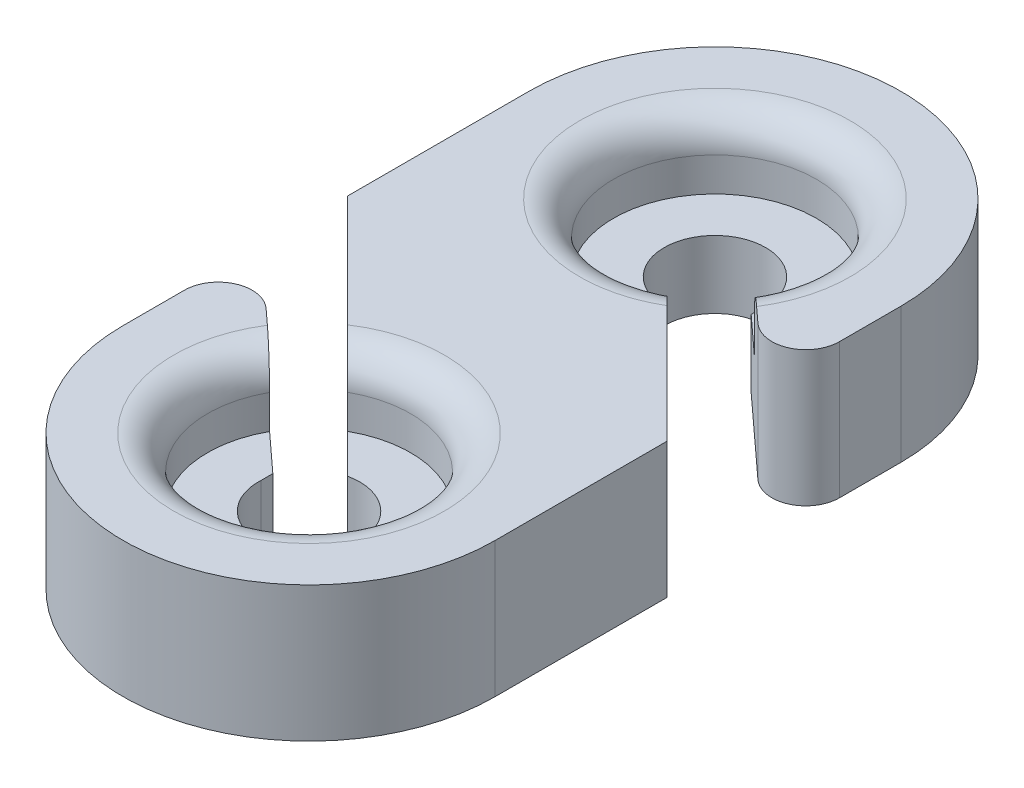
SolidWorks part; units mm, degrees
ref_plane "Front Plane" through (0, 0, 0) normal (0, 0, 1) x (1, 0, 0)
ref_plane "Top Plane" through (0, 0, 0) normal (0, 1, 0) x (1, 0, 0)
ref_plane "Right Plane" through (0, 0, 0) normal (1, 0, 0) x (0, 0, -1)
sketch "Sketch1" plane through (0, 0, 0) normal (0, 1, 0) x (1, 0, 0)
  line L0 (0, 6) -> (0, -6) construction
  line L1 (0, 6) -> (6, 0) construction
  line L2 (0, -6) -> (-6, 0) construction
  line L3 (-6, 0) -> (6, 0) construction
  line L4 (-5.5, 6) -> (-5.5, -6)
  line L5 (5.5, -6) -> (5.5, 6)
  circle A0 centre (0, 6) radius 1.5
  circle A1 centre (0, -6) radius 1.5
  circle A2 centre (0, 6) radius 5.5
  circle A3 centre (0, -6) radius 5.5
  point P3 (0, 0)
  dimension "D1" = 3
  dimension "D3" = 4
  dimension "D2" = 12
sketch "Sketch2" plane through (0, 0, 0) normal (0, 1, 0) x (1, 0, 0)
  line L0 (-5.5, 6) -> (-5.5, 0.6314)
  line L1 (5.5, -6) -> (5.5, -0.9142)
  line L8 (0.5657, -5.4343) -> (-5.4343, 0.5657)
  line L9 (-0.3315, -4.5371) -> (-5.5, 0.6314)
  line L10 (-0.7071, -6.7071) -> (-6.7071, -0.7071)
  line L11 (-1.4977, -5.9165) -> (-5.5, -1.9142) construction
  line L12 (-5.5, -1.9142) -> (-5.5, -6)
  line L13 (-0.7071, 5.2929) -> (5.2929, -0.7071)
  line L14 (0.0835, 4.5023) -> (5.5, -0.9142)
  line L15 (0.7071, 6.7071) -> (6.7071, 0.7071)
  line L16 (1.4977, 5.9165) -> (5.5, 1.9142) construction
  line L17 (5.5, 1.9142) -> (5.5, 6)
  line L18 (-5.5, -1.9142) -> (-1.4977, -5.5723)
  line L19 (-1.4977, -5.5723) -> (-1.4977, -5.9165)
  line L20 (5.5, 1.9142) -> (1.4977, 5.5723)
  line L21 (1.4977, 5.5723) -> (1.4977, 5.9165)
  arc A0 (-5.5, -6) -> (5.5, -6) centre (0, -6) ccw
  arc A1 (5.5, 6) -> (-5.5, 6) centre (0, 6) ccw
  circle A2 centre (0, 6) radius 1.5 construction
  circle A3 centre (0, -6) radius 1.5 construction
  arc A4 (1.4977, 5.9165) -> (0.0835, 4.5023) centre (0, 6) ccw
  arc A5 (-1.4977, -5.9165) -> (-0.3315, -4.5371) centre (0, -6) ccw
  dimension "D1" = 0.8
  dimension "D2" = 1
  dimension "D3" = 1
  dimension "D4" = 1
extrude "Boss-Extrude1" add sketch "Sketch2" along normal blind 4
fillet "Fillet1" radius 1 2 edges at (-5.5, 2, 1.9142) (5.5, 2, -1.9142)
sketch "Sketch3" plane through (0, 4, 0) normal (0, 1, 0) x (1, 0, 0)
  circle A0 centre (0, 6) radius 3
  circle A1 centre (0, -6) radius 3
  dimension "D1" = 6
extrude "Cut-Extrude1" cut sketch "Sketch3" against normal blind 2
fillet "Fillet2" radius 1 2 edges at (-2.0554, 4, -8.1853) (2.1305, 4, 8.1121)
